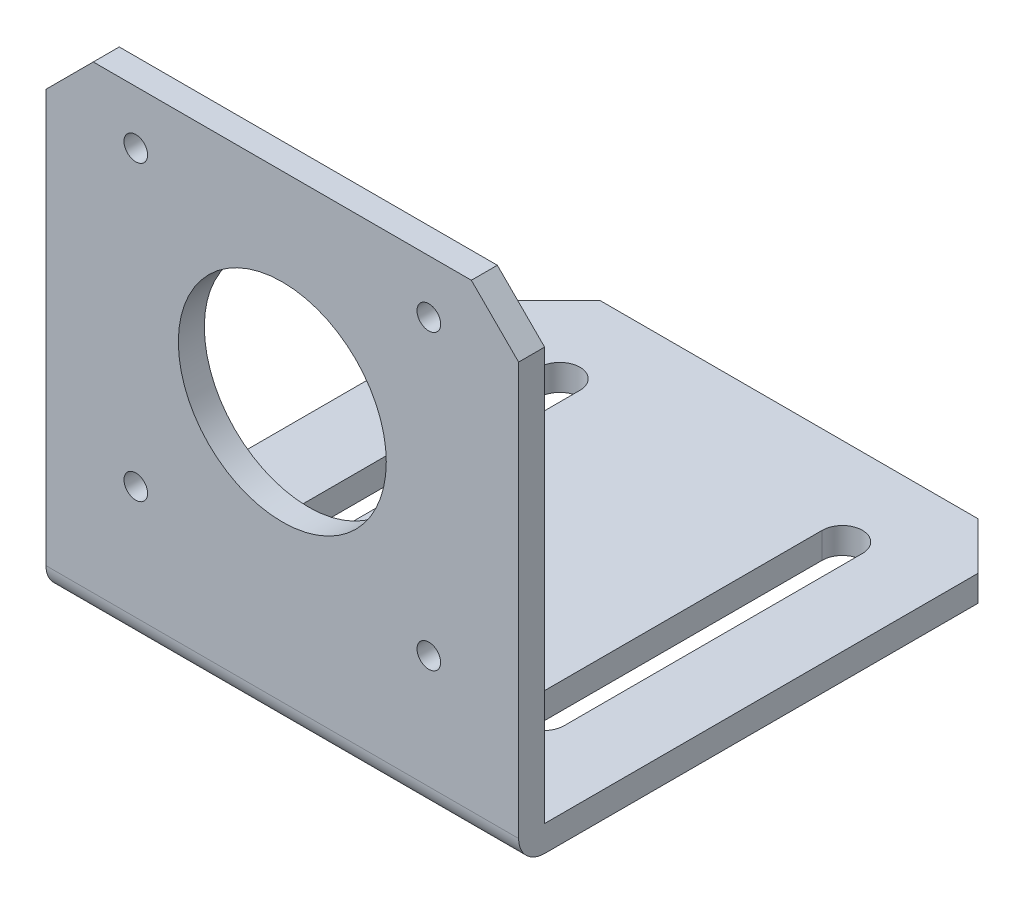
SolidWorks part; units mm, degrees
ref_plane "Front Plane" through (0, 0, 0) normal (0, 0, 1) x (1, 0, 0)
ref_plane "Top Plane" through (0, 0, 0) normal (0, 1, 0) x (1, 0, 0)
ref_plane "Right Plane" through (0, 0, 0) normal (1, 0, 0) x (0, 0, -1)
sketch "Sketch4" plane through (0, 0, 0) normal (1, 0, 0) x (0, 0, -1)
  line L0 (0, 21.15) -> (0, -27.5)
  line L1 (0, -27.5) -> (50.85, -27.5)
  line L2 (6, 21.15) -> (0.5, 21.15) construction
  line L3 (-2.75, 21.15) -> (-2.75, -27.5)
  line L4 (0, -30.25) -> (50.85, -30.25)
  line L5 (-2.75, 21.15) -> (-2.75, -30.25) construction
  line L6 (-2.75, -30.25) -> (50.85, -30.25) construction
  line L7 (0, 21.15) -> (-2.75, 21.15)
  line L8 (50.85, -27.5) -> (50.85, -30.25)
  arc A0 (-2.75, -27.5) -> (0, -30.25) centre (0, -27.5) ccw
  dimension "D2" = 2.75
  dimension "D3" = 51.4
  dimension "D4" = 53.6
  dimension "D1" = 2.75
extrude "Boss-Extrude1" add sketch "Sketch4" along normal mid plane 50
sketch "Sketch5" plane through (0, 0, 2.75) normal (0, 0, 1) x (1, 0, 0)
  circle A0 centre (-15.5, -15.5) radius 1.25 construction
  circle A1 centre (-15.5, 15.5) radius 1.25 construction
  circle A2 centre (15.5, 15.5) radius 1.25 construction
  circle A3 centre (15.5, -15.5) radius 1.25 construction
  circle A4 centre (0, 0) radius 11 construction
  circle A5 centre (-15.5, -15.5) radius 1.25
  circle A6 centre (-15.5, 15.5) radius 1.25
  circle A7 centre (15.5, 15.5) radius 1.25
  circle A8 centre (15.5, -15.5) radius 1.25
  circle A9 centre (0, 0) radius 11
extrude "Cut-Extrude1" cut sketch "Sketch5" against normal through all
sketch "Sketch6" plane through (0, -30.25, 0) normal (0, -1, 0) x (1, 0, 0)
  line L0 (0, 0) -> (0, -50.85) construction
  line L1 (25, 0) -> (-25, 0) construction
  line L2 (25, -50.85) -> (-25, -50.85) construction
  line L3 (-14.945, -9.995) -> (-14.945, -41.55) construction
  line L4 (-12.82, -9.995) -> (-12.82, -41.55)
  line L5 (-17.07, -9.995) -> (-17.07, -41.55)
  line L6 (25, 2.75) -> (-25, 2.75) construction
  line L7 (14.945, -9.995) -> (14.945, -41.55) construction
  line L8 (12.82, -9.995) -> (12.82, -41.55)
  line L9 (17.07, -9.995) -> (17.07, -41.55)
  arc A0 (-12.82, -9.995) -> (-17.07, -9.995) centre (-14.945, -9.995) ccw
  arc A1 (-17.07, -41.55) -> (-12.82, -41.55) centre (-14.945, -41.55) ccw
  arc A2 (12.82, -9.995) -> (17.07, -9.995) centre (14.945, -9.995) cw
  arc A3 (17.07, -41.55) -> (12.82, -41.55) centre (14.945, -41.55) cw
  point P8 (-14.945, -25.7725)
  point P13 (-14.945, -7.87)
  point P14 (-14.945, -43.675)
  point P19 (14.945, -25.7725)
  dimension "D1" = 4.25
  dimension "D2" = 25.64
  dimension "D3" = 10.62
  dimension "D4" = 9.3
extrude "Cut-Extrude2" cut sketch "Sketch6" against normal through all
chamfer "Chamfer1" distance 5 angle 45 4 edges at (25, -28.875, -50.85) (-25, -28.875, -50.85) (25, 21.15, 1.375) (-25, 21.15, 1.375)
